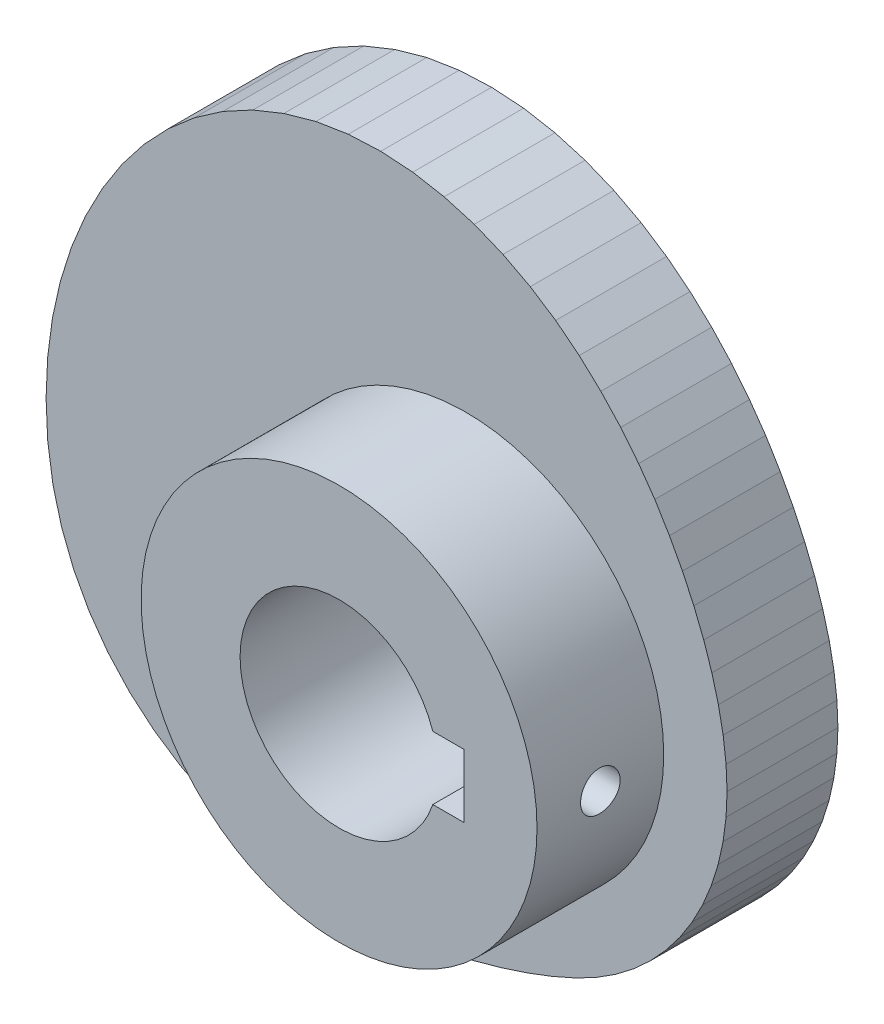
SolidWorks part; units mm, degrees
ref_plane "前视基准面" through (0, 0, 0) normal (0, 0, 1) x (1, 0, 0)
ref_plane "上视基准面" through (0, 0, 0) normal (0, 1, 0) x (1, 0, 0)
ref_plane "右视基准面" through (0, 0, 0) normal (1, 0, 0) x (0, 0, -1)
sketch "草图1" plane through (0, 0, 0) normal (0, 0, 1) x (1, 0, 0)
  line L0 (33, 0) -> (32.877, 2.92)
  line L1 (32.877, 2.92) -> (32.509, 5.918)
  line L2 (32.509, 5.918) -> (31.905, 8.957)
  line L3 (31.905, 8.957) -> (31.082, 12.024)
  line L4 (31.082, 12.024) -> (30.05, 15.108)
  line L5 (30.05, 15.108) -> (28.805, 18.217)
  line L6 (28.805, 18.217) -> (27.368, 21.287)
  line L7 (27.368, 21.287) -> (25.721, 24.347)
  line L8 (25.721, 24.347) -> (23.877, 27.39)
  line L9 (23.877, 27.39) -> (21.833, 30.286)
  line L10 (21.833, 30.286) -> (19.566, 33.114)
  line L11 (19.566, 33.114) -> (17.058, 35.81)
  line L12 (17.058, 35.81) -> (14.33, 38.353)
  line L13 (14.33, 38.353) -> (11.355, 40.699)
  line L14 (11.355, 40.699) -> (8.143, 42.787)
  line L15 (8.143, 42.787) -> (4.705, 44.597)
  line L16 (4.705, 44.597) -> (1.07, 46.077)
  line L17 (1.07, 46.077) -> (-2.738, 47.178)
  line L18 (-2.738, 47.178) -> (-6.695, 47.891)
  line L19 (-6.695, 47.891) -> (-10.736, 48.154)
  line L20 (-10.736, 48.154) -> (-14.831, 47.972)
  line L21 (-14.831, 47.972) -> (-18.921, 47.32)
  line L22 (-18.921, 47.32) -> (-22.957, 46.182)
  line L23 (-22.957, 46.182) -> (-26.882, 44.596)
  line L24 (-26.882, 44.596) -> (-30.655, 42.555)
  line L25 (-30.655, 42.555) -> (-34.232, 40.082)
  line L26 (-34.232, 40.082) -> (-37.587, 37.188)
  line L27 (-37.587, 37.188) -> (-40.651, 33.948)
  line L28 (-40.651, 33.948) -> (-43.421, 30.382)
  line L29 (-43.421, 30.382) -> (-45.899, 26.5)
  line L30 (-45.899, 26.5) -> (-48.034, 22.4)
  line L31 (-48.034, 22.4) -> (-49.804, 18.127)
  line L32 (-49.804, 18.127) -> (-51.194, 13.717)
  line L33 (-51.194, 13.717) -> (-52.195, 9.203)
  line L34 (-52.195, 9.203) -> (-52.798, 4.619)
  line L35 (-52.798, 4.619) -> (-53, 0)
  line L36 (-53, 0) -> (-52.792, -4.538)
  line L37 (-52.792, -4.538) -> (-52.138, -8.965)
  line L38 (-52.138, -8.965) -> (-51.069, -13.013)
  line L39 (-51.069, -13.013) -> (-49.531, -16.93)
  line L40 (-49.531, -16.93) -> (-47.557, -20.575)
  line L41 (-47.557, -20.575) -> (-45.185, -23.874)
  line L42 (-45.185, -23.874) -> (-42.441, -26.865)
  line L43 (-42.441, -26.865) -> (-39.386, -29.472)
  line L44 (-39.386, -29.472) -> (-36.063, -31.683)
  line L45 (-36.063, -31.683) -> (-32.551, -33.456)
  line L46 (-32.551, -33.456) -> (-28.863, -34.852)
  line L47 (-28.863, -34.852) -> (-25.036, -35.873)
  line L48 (-25.036, -35.873) -> (-21.187, -36.513)
  line L49 (-21.187, -36.513) -> (-17.358, -36.81)
  line L50 (-17.358, -36.81) -> (-13.57, -36.793)
  line L51 (-13.57, -36.793) -> (-9.807, -36.517)
  line L52 (-9.807, -36.517) -> (-6.123, -36.017)
  line L53 (-6.123, -36.017) -> (-2.511, -35.329)
  line L54 (-2.511, -35.329) -> (1.018, -34.495)
  line L55 (1.018, -34.495) -> (4.452, -33.532)
  line L56 (4.452, -33.532) -> (7.819, -32.438)
  line L57 (7.819, -32.438) -> (10.907, -31.265)
  line L58 (10.907, -31.265) -> (13.89, -29.95)
  line L59 (13.89, -29.95) -> (16.5, -28.579)
  line L60 (16.5, -28.579) -> (18.928, -27.032)
  line L61 (18.928, -27.032) -> (21.212, -25.279)
  line L62 (21.212, -25.279) -> (23.335, -23.335)
  line L63 (23.335, -23.335) -> (25.279, -21.212)
  line L64 (25.279, -21.212) -> (27.032, -18.928)
  line L65 (27.032, -18.928) -> (28.579, -16.5)
  line L66 (28.579, -16.5) -> (29.908, -13.946)
  line L67 (29.908, -13.946) -> (31.01, -11.287)
  line L68 (31.01, -11.287) -> (31.876, -8.541)
  line L69 (31.876, -8.541) -> (32.499, -5.73)
  line L70 (32.499, -5.73) -> (32.874, -2.876)
  line L71 (32.874, -2.876) -> (33, 0)
extrude "凸台-拉伸1" add sketch "草图1" along normal blind 14
sketch "草图2" plane through (0, 0, 0) normal (0, 0, 1) x (1, 0, 0)
  circle A0 centre (0, 0) radius 25
extrude "凸台-拉伸2" add sketch "草图2" along normal blind 30
sketch "草图3" plane through (0, 0, 0) normal (0, 0, 1) x (1, 0, 0)
  circle A0 centre (0, 0) radius 12.5
extrude "切除-拉伸1" cut sketch "草图3" along normal through all
sketch "草图4" plane through (0, 0, 0) normal (0, 0, 1) x (1, 0, 0)
  line L0 (0, -4) -> (15.8, -4)
  line L1 (15.8, -4) -> (15.8, 4)
  line L2 (15.8, 4) -> (0, 4)
  line L3 (0, 4) -> (0, -4)
extrude "切除-拉伸2" cut sketch "草图4" along normal through all
ref_plane "基准面1" through (25, 0, 0) normal (1, 0, 0) x (0, 0, -1)
sketch "草图5" plane through (25, 0, 0) normal (1, 0, 0) x (0, 0, -1)
  circle A0 centre (-22, 0) radius 2.5
extrude "切除-拉伸3" cut sketch "草图5" against normal blind 12.6
